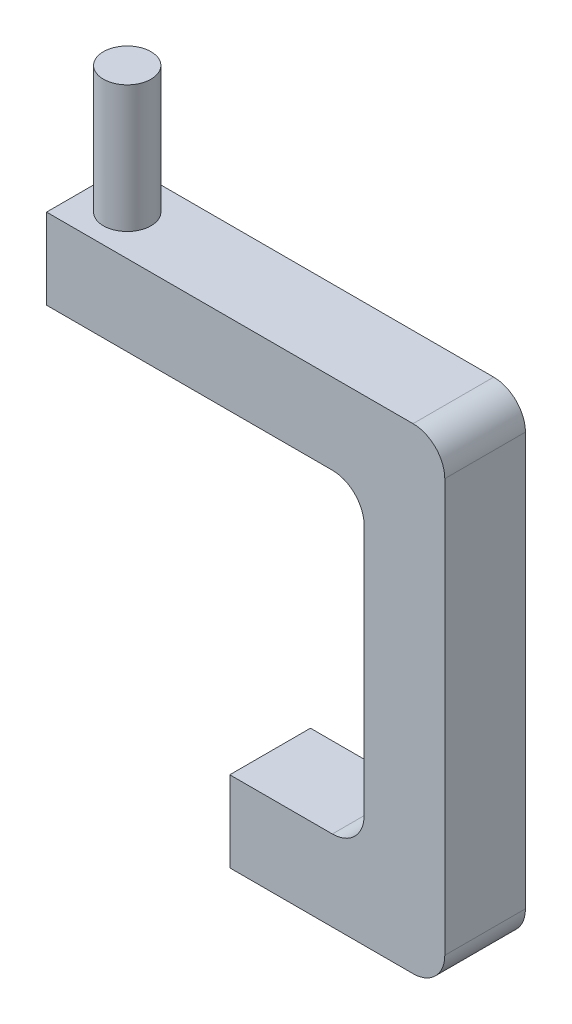
SolidWorks part; units mm, degrees
ref_plane "Front Plane" through (0, 0, 0) normal (0, 0, 1) x (1, 0, 0)
ref_plane "Top Plane" through (0, 0, 0) normal (0, 1, 0) x (1, 0, 0)
ref_plane "Right Plane" through (0, 0, 0) normal (1, 0, 0) x (0, 0, -1)
sketch "Sketch1" plane through (0, 0, 0) normal (0, 0, 1) x (1, 0, 0)
  line L1 (-12.7, 75) -> (12.7, 75)
  line L2 (-12.7, 75) -> (-12.7, -75)
  line L3 (-12.7, -75) -> (12.7, -75)
  line L4 (12.7, 75) -> (12.7, -75)
  line L5 (-12.7, 75) -> (12.7, -75) construction
  line L6 (-12.7, -75) -> (12.7, 75) construction
  line L7 (-12.7, 75) -> (-112.7, 75)
  line L9 (-12.7, 49.6) -> (-112.7, 49.6)
  line L10 (-112.7, 75) -> (-112.7, 49.6)
  line L11 (-12.7, -75) -> (-55, -75)
  line L13 (-11.5673, -49.6) -> (-55, -49.6)
  line L14 (-55, -75) -> (-55, -49.6)
  point P0 (0, 0)
  dimension "D1" = 25.4
  dimension "D2" = 25.4
  dimension "D3" = 25.4
  dimension "D4" = 150
  dimension "D5" = 100
  dimension "D6" = 67.7
extrude "Boss-Extrude1" add sketch "Sketch1" along normal blind 25.4 contours L7 L10 L9 L2 | L4 L1 L2 L3 | L14 L11 L2 L13
sketch "Sketch2" plane through (0, 75, 0) normal (0, 1, 0) x (1, 0, 0)
  line L0 (-112.7, -25.4) -> (-87.3, 0) construction
  line L1 (12.7, 0) -> (-112.7, 0) construction
  line L2 (-87.3, 0) -> (-112.7, 0)
  line L3 (-112.7, -25.4) -> (-112.7, 0) construction
  circle A0 centre (-100, -12.7) radius 7.5
  dimension "D1" = 15
extrude "Boss-Extrude2" add sketch "Sketch2" along normal blind 40 contours A0 L0 | L0 A0
sketch "Sketch3" plane through (-55, 0, 0) normal (-1, 0, 0) x (0, 0, 1)
  line L0 (25.4, -49.6) -> (0, -75) construction
  circle A0 centre (12.7, -62.3) radius 7.5
  dimension "D1" = 15
extrude "Cut-Extrude2" cut sketch "Sketch3" against normal blind 30 contours L0 A0 | L0 A0
fillet "Fillet1" radius 10 4 edges at (-12.7, 49.6, 12.7) (12.7, 75, 12.7) (12.7, -75, 12.7) (-12.7, -49.6, 12.7)
